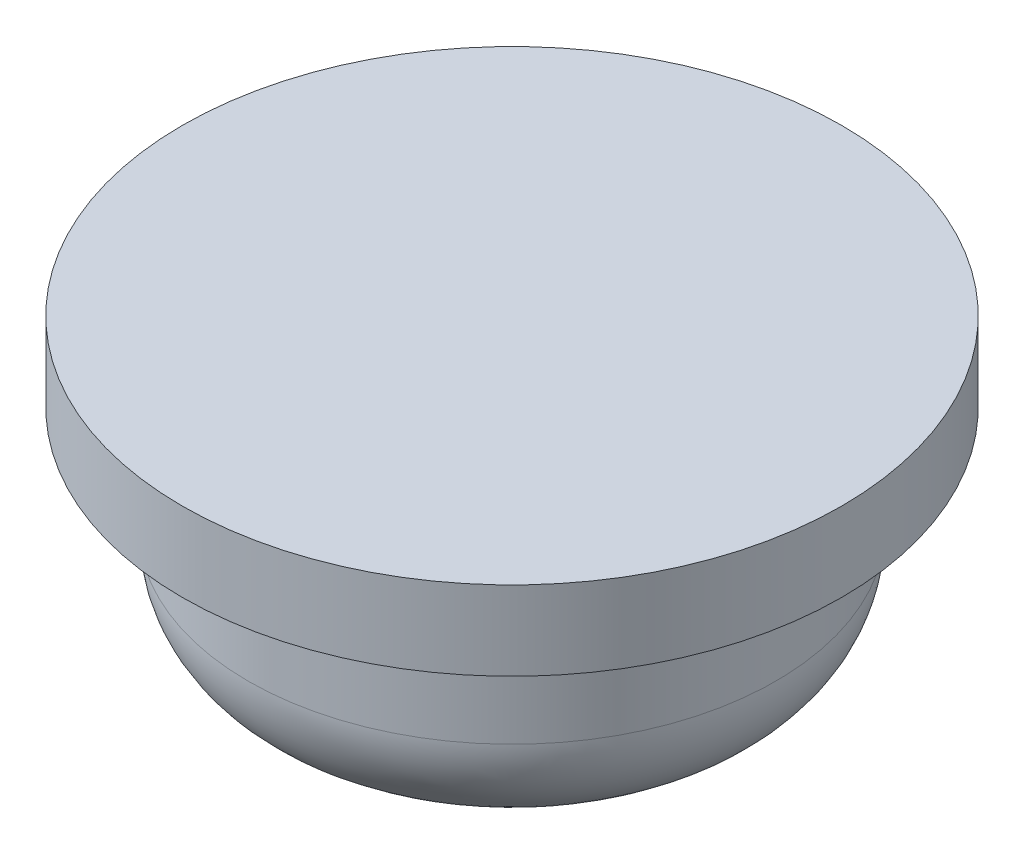
SolidWorks part; units mm, degrees
ref_plane "Спереди" through (0, 0, 0) normal (0, 0, 1) x (1, 0, 0)
ref_plane "Сверху" through (0, 0, 0) normal (0, 1, 0) x (1, 0, 0)
ref_plane "Справа" through (0, 0, 0) normal (1, 0, 0) x (0, 0, -1)
sketch "Эскиз1" plane through (0, 0, 0) normal (0, 1, 0) x (1, 0, 0)
  circle A0 centre (0, 0) radius 2
  dimension "D1" = 4
extrude "Бобышка-Вытянуть1" add sketch "Эскиз1" along normal blind 1.6
sketch "Эскиз2" plane through (0, 1.6, 0) normal (0, 1, 0) x (1, 0, 0)
  circle A0 centre (0, 0) radius 2.5
  circle A1 centre (0, 0) radius 2
  circle A2 centre (0, 0) radius 2
  circle M2 centre (0, 0) radius 2
  dimension "D1" = 0
  dimension "D2" = 0.5
extrude "Бобышка-Вытянуть2" add sketch "Эскиз2" along normal blind 0.6 contours M2 | A0 M2
fillet "Скругление1" radius 0.8 1 edges at (0, 0, 2)
